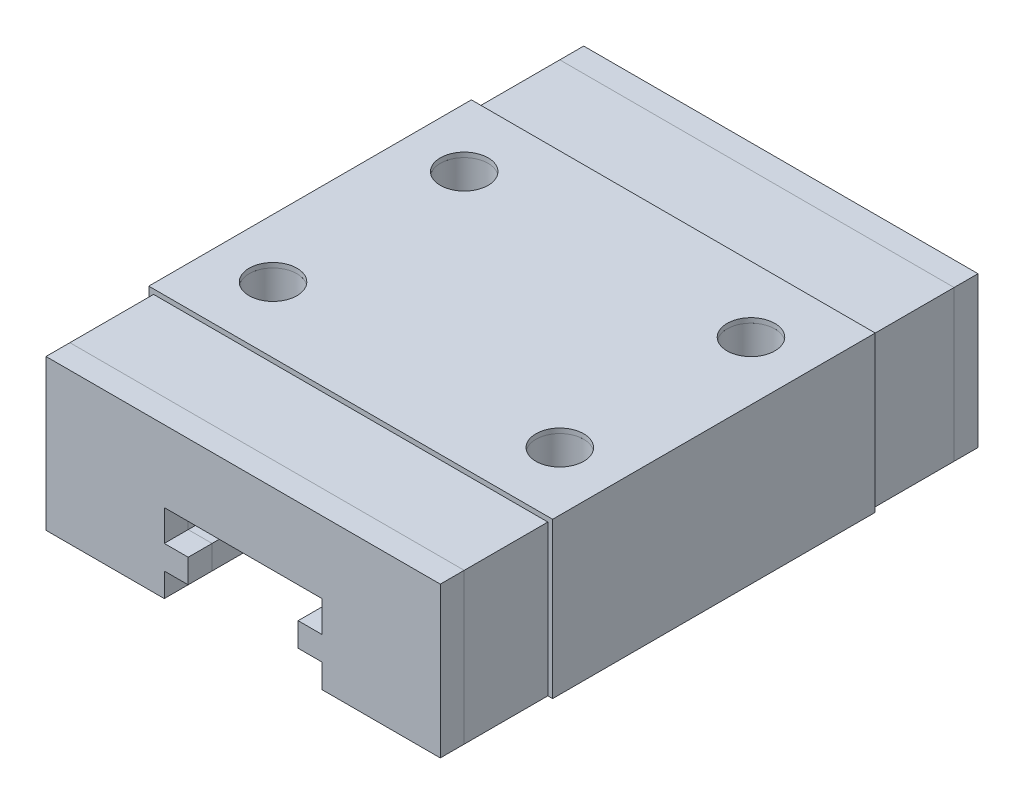
SolidWorks part; units mm, degrees
material "1060 合金"
ref_plane "前视基准面" through (0, 0, 0) normal (0, 0, 1) x (1, 0, 0)
ref_plane "上视基准面" through (0, 0, 0) normal (0, 1, 0) x (1, 0, 0)
ref_plane "右视基准面" through (0, 0, 0) normal (1, 0, 0) x (0, 0, -1)
sketch "草图1" plane through (0, 0, 0) normal (0, 0, 1) x (1, 0, 0)
  line L0 (0, 0) -> (0, 6.3)
  line L1 (0, 6.3) -> (16.5, 6.3)
  line L2 (16.5, 6.3) -> (16.5, 0)
  line L3 (16.5, 0) -> (11.55, 0)
  line L4 (0, 0) -> (4.95, 0)
  line L5 (4.95, 0) -> (4.95, 1)
  line L6 (4.95, 1) -> (5.95, 1)
  line L7 (5.95, 1) -> (5.95, 2)
  line L8 (5.95, 2) -> (4.95, 2)
  line L9 (4.95, 2) -> (4.95, 3.3)
  line L10 (4.95, 3.3) -> (11.55, 3.3)
  line L11 (11.55, 3.3) -> (11.55, 2)
  line L12 (11.55, 2) -> (10.55, 2)
  line L13 (10.55, 2) -> (10.55, 1)
  line L14 (10.55, 1) -> (11.55, 1)
  line L15 (11.55, 1) -> (11.55, 0)
  line L16 (8.25, 6.3) -> (8.25, 0) construction
  dimension "D1" = 16.5
  dimension "D2" = 6.3
  dimension "D3" = 6.6
  dimension "D4" = 3
  dimension "D5" = 1.3
  dimension "D6" = 1
  dimension "D7" = 1
extrude "凸台-拉伸1" add sketch "草图1" along normal blind 1
sketch "草图2" plane through (0, 0, 1) normal (0, 0, 1) x (1, 0, 0)
  line L0 (4.95, 0) -> (4.95, 1)
  line L1 (4.95, 1) -> (5.95, 1)
  line L2 (5.95, 1) -> (5.95, 2)
  line L3 (5.95, 2) -> (4.95, 2)
  line L4 (4.95, 2) -> (4.95, 3.3)
  line L5 (4.95, 3.3) -> (11.55, 3.3)
  line L6 (11.55, 3.3) -> (11.55, 2)
  line L7 (11.55, 2) -> (10.55, 2)
  line L8 (10.55, 2) -> (10.55, 1)
  line L9 (10.55, 1) -> (11.55, 1)
  line L10 (11.55, 1) -> (11.55, 0)
  line L11 (11.55, 0) -> (16.5, 0)
  line L13 (16.5, 0) -> (16.5, 6.3)
  line L14 (16.5, 6.3) -> (0, 6.3)
  line L15 (0, 6.3) -> (0, 0)
  line L16 (0, 0) -> (4.95, 0) construction
  line L17 (0, 0) -> (4.95, 0)
extrude "凸台-拉伸2" add sketch "草图2" along normal blind 20.5 separate body
sketch "草图3" plane through (0, 0, 21.5) normal (0, 0, 1) x (1, 0, 0)
  line L17 (0, 0) -> (4.95, 0)
  line L18 (4.95, 0) -> (4.95, 1)
  line L19 (4.95, 1) -> (5.95, 1)
  line L20 (5.95, 1) -> (5.95, 2)
  line L21 (5.95, 2) -> (4.95, 2)
  line L22 (4.95, 2) -> (4.95, 3.3)
  line L23 (4.95, 3.3) -> (11.55, 3.3)
  line L24 (11.55, 3.3) -> (11.55, 2)
  line L25 (11.55, 2) -> (10.55, 2)
  line L26 (10.55, 2) -> (10.55, 1)
  line L27 (10.55, 1) -> (11.55, 1)
  line L28 (11.55, 1) -> (11.55, 0)
  line L29 (11.55, 0) -> (16.5, 0)
  line L30 (16.5, 0) -> (16.5, 6.3)
  line L31 (16.5, 6.3) -> (0, 6.3)
  line L32 (0, 6.3) -> (0, 0)
  line L33 (0, 0) -> (4.95, 0)
  line L34 (4.95, 0) -> (4.95, 1)
  line L35 (4.95, 1) -> (5.95, 1)
  line L36 (5.95, 1) -> (5.95, 2)
  line L37 (5.95, 2) -> (4.95, 2)
  line L38 (4.95, 2) -> (4.95, 3.3)
  line L39 (4.95, 3.3) -> (11.55, 3.3)
  line L40 (11.55, 3.3) -> (11.55, 2)
  line L41 (11.55, 2) -> (10.55, 2)
  line L42 (10.55, 2) -> (10.55, 1)
  line L43 (10.55, 1) -> (11.55, 1)
  line L44 (11.55, 1) -> (11.55, 0)
  line L45 (11.55, 0) -> (16.5, 0)
  line L46 (16.5, 0) -> (16.5, 6.3)
  line L47 (16.5, 6.3) -> (0, 6.3)
  line L48 (0, 6.3) -> (0, 0)
  dimension "D1" = 0
extrude "凸台-拉伸3" add sketch "草图3" along normal blind 1
ref_plane "基准面1" through (0, 0, 4.5) normal (0, 0, 1) x (1, 0, 0)
fillet "圆角1" radius 0.25 12 edges at (4.95, 0, 0.5) (11.55, 0, 0.5) (11.55, 3.3, 0.5) (4.95, 3.3, 0.5) (4.95, 2, 0.5) (5.95, 2, 0.5) (5.95, 1, 0.5) (4.95, 1, 0.5) (11.55, 1, 0.5) (11.55, 2, 0.5) (10.55, 1, 0.5) (10.55, 2, 0.5)
sketch "草图4" plane through (0, 0, 4.5) normal (0, 0, 1) x (1, 0, 0)
  line L0 (8.25, 6.3) -> (8.25, 3.3) construction
  line L1 (0, 0) -> (-0.2, 0)
  line L2 (-0.2, 0) -> (-0.2, 6.5)
  line L3 (-0.2, 6.5) -> (8.25, 6.5)
  line L4 (8.25, 6.5) -> (8.25, 6.3)
  line L5 (8.25, 6.3) -> (0, 6.3)
  line L6 (0, 6.3) -> (0, 0)
  line L7 (16.5, 6.3) -> (0, 6.3) construction
  line L8 (4.95, 3.3) -> (11.55, 3.3) construction
  line L9 (0, 6.3) -> (0, 0) construction
  line L10 (16.5, 6.3) -> (16.5, 0)
  line L11 (8.25, 6.3) -> (16.5, 6.3)
  line L12 (8.25, 6.5) -> (8.25, 6.3)
  line L13 (16.7, 6.5) -> (8.25, 6.5)
  line L14 (16.7, 0) -> (16.7, 6.5)
  line L15 (16.5, 0) -> (16.7, 0)
  dimension "D1" = 0.2
  dimension "D2" = 0.2
extrude "凸台-拉伸4" add sketch "草图4" along normal blind 13.5 contours L10 L15 L14 L13 L4 L11
sketch "草图5" plane through (0, 6.5, 0) normal (0, 1, 0) x (1, 0, 0)
  line L0 (-0.2, -11.25) -> (16.7, -11.25) construction
  line L1 (-0.2, -18) -> (-0.2, -4.5) construction
  line L2 (-0.2, -18) -> (-0.2, -4.5) construction
  line L3 (8.25, -4.5) -> (8.25, -18) construction
  line L6 (16.7, -18) -> (16.7, -4.5) construction
  line L7 (16.7, -4.5) -> (-0.2, -4.5) construction
  line L8 (16.7, -18) -> (-0.2, -18) construction
  circle A0 centre (2.25, -7.25) radius 1
  circle A1 centre (2.25, -15.25) radius 1
  circle A2 centre (14.25, -15.25) radius 1
  circle A3 centre (14.25, -7.25) radius 1
  dimension "D2" = 12
  dimension "D1" = 2
  dimension "D3" = 8
extrude "切除-拉伸1" cut sketch "草图5" against normal blind 4 contours A1 | A2 | A3 | A0
ref_plane "基准面2" through (8.25, 0, 0) normal (1, 0, 0) x (0, 0, -1)
